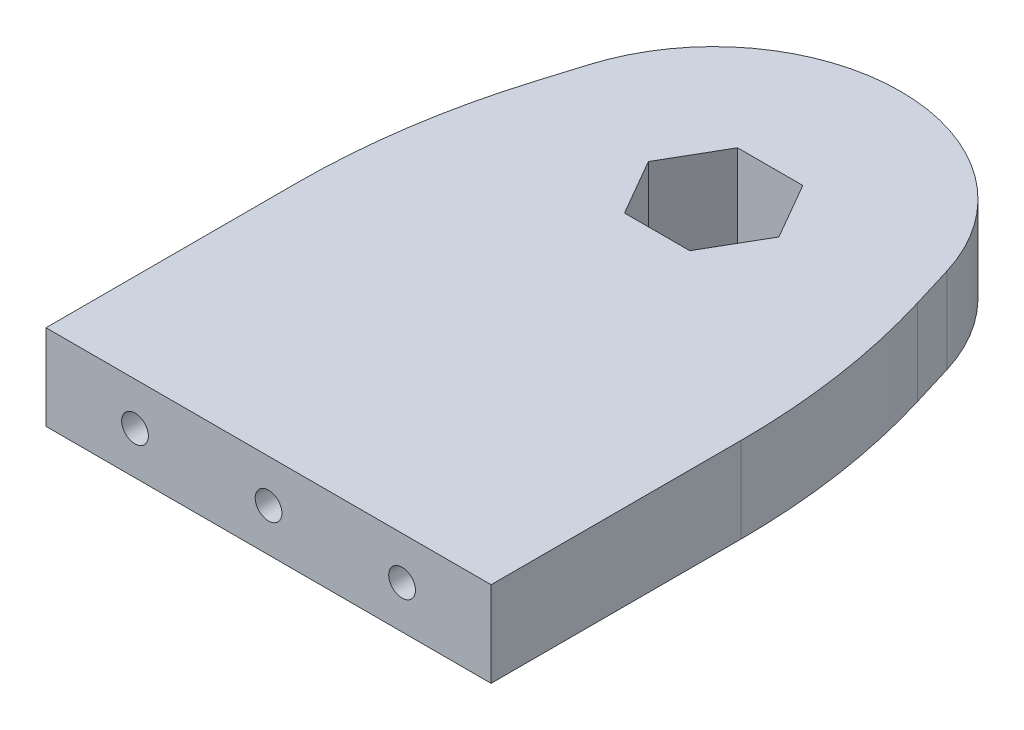
SolidWorks part; units mm, degrees
ref_plane "Alzado" through (0, 0, 0) normal (0, 0, 1) x (1, 0, 0)
ref_plane "Planta" through (0, 0, 0) normal (0, 1, 0) x (1, 0, 0)
ref_plane "Vista lateral" through (0, 0, 0) normal (1, 0, 0) x (0, 0, -1)
sketch "Croquis1" plane through (0, 0, 0) normal (0, 1, 0) x (1, 0, 0)
  line L5 (-25, 20) -> (-20.0883, 36.1206)
  line L6 (-25, 20) -> (25, 20)
  line L7 (-25, 20) -> (-25, -20)
  line L8 (-25, -20) -> (25, -20)
  line L9 (25, 20) -> (25, -20)
  line L10 (-25, 20) -> (25, -20) construction
  line L11 (-25, -20) -> (25, 20) construction
  line L12 (25, 20) -> (20.0883, 36.1206)
  circle A0 centre (0, 30) radius 21
  point P0 (0, 0)
  dimension "D3" = 42
  dimension "D1" = 50
  dimension "D2" = 40
  dimension "D4" = 30
extrude "Saliente-Extruir1" add sketch "Croquis1" along normal blind 9.6 contours A0 L6 L7 L8 L9 | L6 A0 | A0 L6 L12 | L6 A0 | A0 L5 L6
sketch "Croquis2" plane through (0, 9.6, 0) normal (0, 1, 0) x (1, 0, 0)
  circle A0 centre (0, 30) radius 16
  dimension "D1" = 32
extrude "Cortar-Extruir1" cut sketch "Croquis2" against normal through all
fillet "Redondeo1" radius 80 2 edges at (25, 4.8, -20) (-25, 4.8, -20)
sketch "Croquis3" plane through (0, 0, 20) normal (0, 0, 1) x (1, 0, 0)
  line L0 (-25, 4.8) -> (25, 4.8) construction
  line L1 (-25, 9.6) -> (-25, 0) construction
  line L2 (25, 9.6) -> (25, 0) construction
  circle A0 centre (0, 4.8) radius 1.5
  dimension "D1" = 3
extrude "Cortar-Extruir2" cut sketch "Croquis3" against normal blind 15
pattern_linear "MatrizL1" count 2 spacing 15 along (1, 0, 0) count 2 spacing 15 along (-1, 0, 0) of "Cortar-Extruir2"
sketch "Sketch1" plane through (0, 9.6, 0) normal (0, 1, 0) x (1, 0, 0)
  line L1 (-2.5, 39.5) -> (2.5, 39.5)
  line L2 (-2.5, 39.5) -> (-2.5, 34.5)
  line L3 (-2.5, 34.5) -> (2.5, 34.5)
  line L4 (2.5, 39.5) -> (2.5, 34.5)
  line L5 (-2.5, 39.5) -> (2.5, 34.5) construction
  line L6 (-2.5, 34.5) -> (2.5, 39.5) construction
  circle A0 centre (0, 30) radius 7
  circle A1 centre (0, 30) radius 16 construction
  circle A2 centre (0, 30) radius 16
  point P3 (0, 37)
  circle M4 centre (0, 30) radius 16
  dimension "D1" = 14
  dimension "D2" = 5
extrude "Boss-Extrude1" add sketch "Sketch1" against normal up to surface (9.6 mm away) contours A0 L2 L1 L4 M4 up to face at (0, 0, -14)
sketch "Sketch3" plane through (0, 9.6, 0) normal (0, 1, 0) x (1, 0, 0)
  circle A0 centre (0, 30) radius 10
  dimension "D1" = 20
extrude "Boss-Extrude2" add sketch "Sketch3" against normal up to surface (9.6 mm away) up to face at (0, 0, -15.7929)
sketch "Sketch2" plane through (0, 9.6, 0) normal (0, 1, 0) x (1, 0, 0)
  line L1 (3.6662, 36.35) -> (-3.6662, 36.35)
  line L2 (-3.6662, 36.35) -> (-7.3323, 30)
  line L3 (-7.3323, 30) -> (-3.6662, 23.65)
  line L4 (-3.6662, 23.65) -> (3.6662, 23.65)
  line L5 (3.6662, 23.65) -> (7.3323, 30)
  line L6 (7.3323, 30) -> (3.6662, 36.35)
  circle A0 centre (0, 30) radius 6.35 construction
  point P1 (0, 0)
  point P10 (0, 30)
  point P11 (0, 0)
  point P14 (0, 30)
  dimension "D1" = 12.7
extrude "Cut-Extrude2" cut sketch "Sketch2" against normal blind 10
